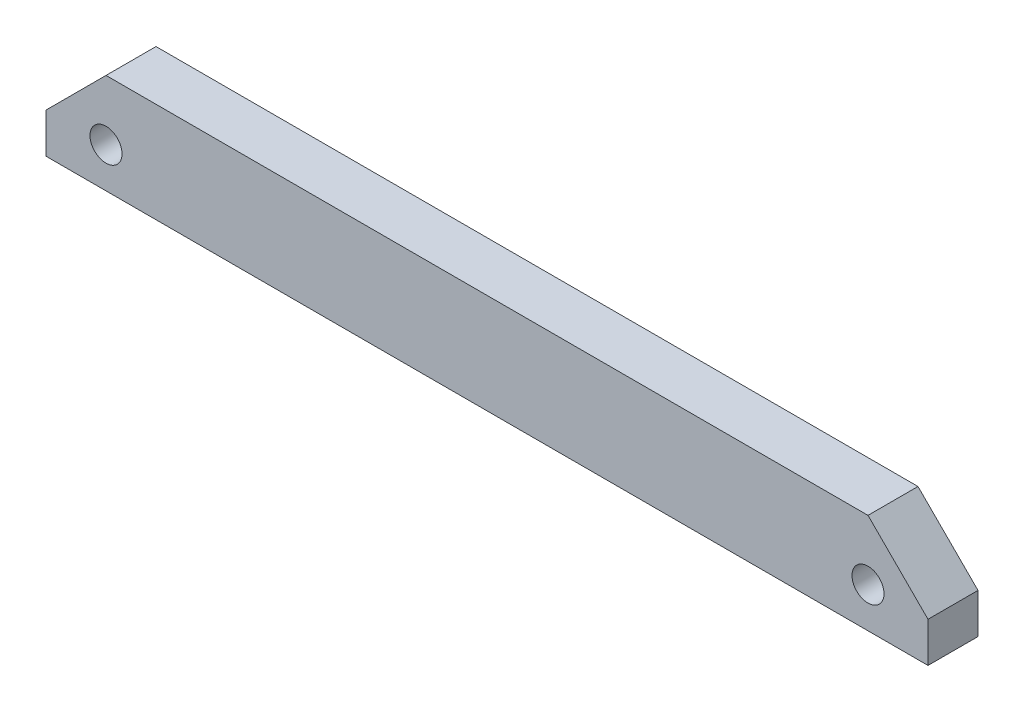
SolidWorks part; units mm, degrees
material "ABS"
ref_plane "Płaszczyzna przednia" through (0, 0, 0) normal (0, 0, 1) x (1, 0, 0)
ref_plane "Płaszczyzna górna" through (0, 0, 0) normal (0, 1, 0) x (1, 0, 0)
ref_plane "Płaszczyzna prawa" through (0, 0, 0) normal (1, 0, 0) x (0, 0, -1)
sketch "Szkic1" plane through (0, 0, 0) normal (0, 0, 1) x (1, 0, 0)
  line L0 (-44.1, 0) -> (44.1, 0)
  line L1 (-44.1, 0) -> (-44.1, 4)
  line L2 (-44.1, 4) -> (-38.1, 10)
  line L3 (44.1, 0) -> (44.1, 4)
  line L4 (44.1, 4) -> (38.1, 10)
  line L5 (38.1, 10) -> (-38.1, 10)
  point P4 (0, 0)
  dimension "D1" = 88.2
  dimension "D2" = 4
  dimension "D3" = 4
  dimension "D4" = 10
  dimension "D5" = 45
extrude "Dodanie-wyciągnięcie1" add sketch "Szkic1" along normal blind 5
sketch "Szkic2" plane through (0, 0, 5) normal (0, 0, 1) x (1, 0, 0)
  line L0 (-44.1, 0) -> (-38.1, 0) construction
  line L1 (-44.1, 0) -> (44.1, 0) construction
  line L2 (-38.1, 0) -> (-38.1, 4) construction
  line L3 (0, 0) -> (0, 10) construction
  line L4 (38.1, 10) -> (-38.1, 10) construction
  circle A0 centre (-38.1, 4) radius 1.6
  circle A1 centre (38.1, 4) radius 1.6
  dimension "D1" = 3.2
  dimension "D2" = 6
  dimension "D3" = 4
extrude "Wytnij-wyciągnięcie1" cut sketch "Szkic2" against normal through all
equation "\"Width\"=10"
equation "\"D2@Szkic2\"=\"Width\"/2+1"
equation "\"D3@Szkic2\"=\"Width\"/2-1"
